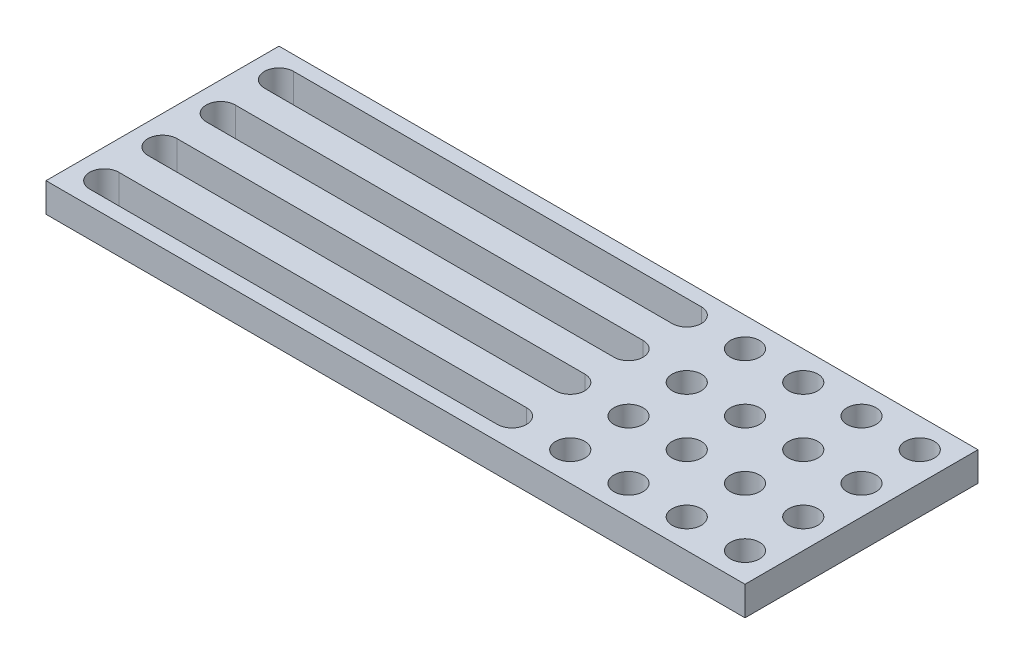
SolidWorks part; units mm, degrees
ref_plane "Front Plane" through (0, 0, 0) normal (0, 0, 1) x (1, 0, 0)
ref_plane "Top Plane" through (0, 0, 0) normal (0, 1, 0) x (1, 0, 0)
ref_plane "Right Plane" through (0, 0, 0) normal (1, 0, 0) x (0, 0, -1)
sketch "Sketch1" plane through (0, 0, 0) normal (0, 1, 0) x (1, 0, 0)
  line L0 (-76.2, 19.05) -> (76.2, 19.05) construction
  line L1 (-76.2, -25.4) -> (76.2, -25.4)
  line L2 (-76.2, -25.4) -> (-76.2, 25.4)
  line L3 (-76.2, 25.4) -> (76.2, 25.4)
  line L4 (76.2, -25.4) -> (76.2, 25.4)
  line L5 (-76.2, -25.4) -> (76.2, 25.4) construction
  line L6 (-76.2, 25.4) -> (76.2, -25.4) construction
  line L7 (-69.85, 22.225) -> (19.05, 22.225)
  line L8 (19.05, 3.175) -> (-69.85, 3.175)
  line L9 (19.05, 15.875) -> (-69.85, 15.875)
  line L10 (-69.85, 9.525) -> (19.05, 9.525)
  line L11 (19.05, -9.525) -> (-69.85, -9.525)
  line L12 (-69.85, -3.175) -> (19.05, -3.175)
  line L13 (19.05, -22.225) -> (-69.85, -22.225)
  line L14 (-69.85, -15.875) -> (19.05, -15.875)
  arc A0 (-69.85, 22.225) -> (-69.85, 15.875) centre (-69.85, 19.05) ccw
  arc A1 (19.05, 15.875) -> (19.05, 22.225) centre (19.05, 19.05) ccw
  circle A2 centre (31.75, 19.05) radius 3.175
  circle A3 centre (44.45, 19.05) radius 3.175
  circle A4 centre (57.15, 19.05) radius 3.175
  arc A5 (-69.85, 9.525) -> (-69.85, 3.175) centre (-69.85, 6.35) ccw
  arc A6 (19.05, 3.175) -> (19.05, 9.525) centre (19.05, 6.35) ccw
  circle A7 centre (31.75, 6.35) radius 3.175
  circle A8 centre (44.45, 6.35) radius 3.175
  circle A9 centre (57.15, 6.35) radius 3.175
  circle A10 centre (69.85, 6.35) radius 3.175
  arc A11 (-69.85, -3.175) -> (-69.85, -9.525) centre (-69.85, -6.35) ccw
  arc A12 (19.05, -9.525) -> (19.05, -3.175) centre (19.05, -6.35) ccw
  circle A13 centre (31.75, -6.35) radius 3.175
  circle A14 centre (44.45, -6.35) radius 3.175
  circle A15 centre (57.15, -6.35) radius 3.175
  circle A16 centre (69.85, -6.35) radius 3.175
  arc A17 (-69.85, -15.875) -> (-69.85, -22.225) centre (-69.85, -19.05) ccw
  arc A18 (19.05, -22.225) -> (19.05, -15.875) centre (19.05, -19.05) ccw
  circle A19 centre (31.75, -19.05) radius 3.175
  circle A20 centre (69.85, 19.05) radius 3.175
  circle A21 centre (44.45, -19.05) radius 3.175
  circle A22 centre (57.15, -19.05) radius 3.175
  circle A23 centre (69.85, -19.05) radius 3.175
  point P0 (0, 0)
  dimension "D4" = 6.35
  dimension "D7" = 6.35
  dimension "D1" = 50.8
  dimension "D2" = 152.4
  dimension "D3" = 6.35
  dimension "D5" = 6.35
  dimension "D6" = 88.9
  dimension "D8" = 12.7
  dimension "D9" = 4
  dimension "D10" = 4
extrude "Boss-Extrude1" add sketch "Sketch1" along normal blind 6.35
